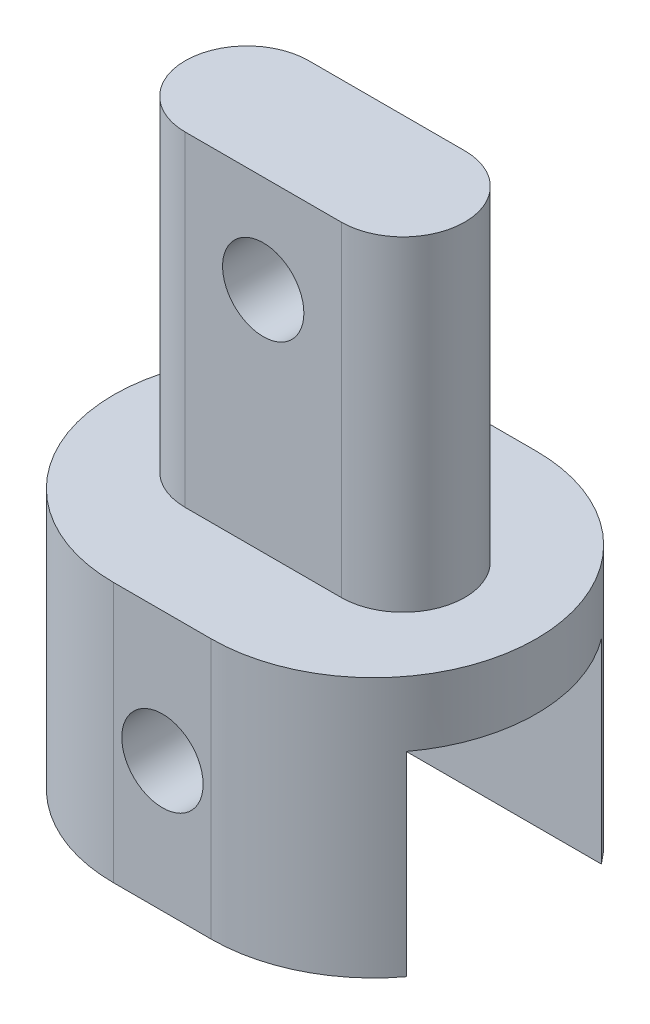
SolidWorks part; units mm, degrees
ref_plane "前视基准面" through (0, 0, 0) normal (0, 0, 1) x (1, 0, 0)
ref_plane "上视基准面" through (0, 0, 0) normal (0, 1, 0) x (1, 0, 0)
ref_plane "右视基准面" through (0, 0, 0) normal (1, 0, 0) x (0, 0, -1)
sketch "草图1" plane through (0, 0, 0) normal (0, 1, 0) x (1, 0, 0)
  line L0 (-1.5, 0) -> (1.5, 0) construction
  line L1 (-1.5, 5) -> (1.5, 5)
  line L2 (-1.5, -5) -> (1.5, -5)
  arc A0 (-1.5, 5) -> (-1.5, -5) centre (-1.5, 0) ccw
  arc A1 (1.5, -5) -> (1.5, 5) centre (1.5, 0) ccw
  point P2 (0, 0)
  dimension "D1" = 10
  dimension "D2" = 3
extrude "凸台-拉伸1" add sketch "草图1" along normal blind 8
sketch "草图2" plane through (0, 8, 0) normal (0, 1, 0) x (1, 0, 0)
  line L0 (-2.4, 0) -> (2.4, 0) construction
  line L1 (-2.4, 1.9) -> (2.4, 1.9)
  line L2 (-2.4, -1.9) -> (2.4, -1.9)
  arc A0 (-2.4, 1.9) -> (-2.4, -1.9) centre (-2.4, 0) ccw
  arc A1 (2.4, -1.9) -> (2.4, 1.9) centre (2.4, 0) ccw
  point P2 (0, 0)
  dimension "D1" = 3.8
  dimension "D2" = 4.8
extrude "凸台-拉伸2" add sketch "草图2" along normal blind 10
sketch "草图3" plane through (0, 0, 1.9) normal (0, 0, 1) x (1, 0, 0)
  line L0 (-2.4, 18) -> (2.4, 18) construction
  circle A0 centre (0, 15) radius 1.25
  dimension "D1" = 2.5
  dimension "D2" = 3
extrude "切除-拉伸1" cut sketch "草图3" against normal blind 6
sketch "草图4" plane through (0, 0, 0) normal (0, -1, 0) x (1, 0, 0)
  line L1 (-12.5596, 3) -> (12.5596, 3)
  line L2 (-12.5596, 3) -> (-12.5596, -3)
  line L3 (-12.5596, -3) -> (12.5596, -3)
  line L4 (12.5596, 3) -> (12.5596, -3)
  line L5 (-12.5596, 3) -> (12.5596, -3) construction
  line L6 (-12.5596, -3) -> (12.5596, 3) construction
  point P0 (0, 0)
  dimension "D1" = 6
extrude "切除-拉伸2" cut sketch "草图4" against normal blind 6
sketch "草图5" plane through (0, 0, 5) normal (0, 0, 1) x (1, 0, 0)
  line L0 (-2.4, 8) -> (2.4, 8) construction
  circle A0 centre (0, 4) radius 1.25
  dimension "D1" = 4
  dimension "D2" = 2.5
extrude "切除-拉伸3" cut sketch "草图5" against normal through all
